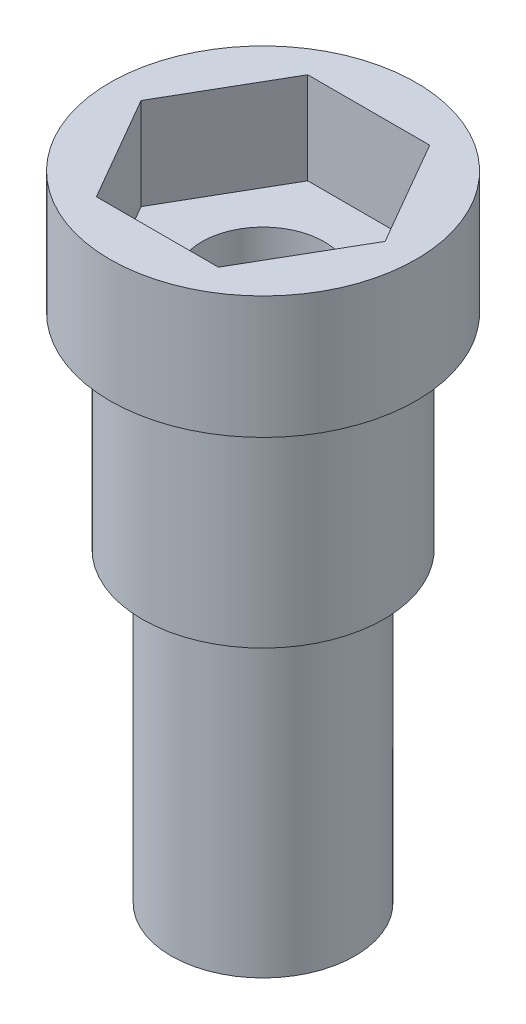
SolidWorks part; units mm, degrees
ref_plane "Front Plane" through (0, 0, 0) normal (0, 0, 1) x (1, 0, 0)
ref_plane "Top Plane" through (0, 0, 0) normal (0, 1, 0) x (1, 0, 0)
ref_plane "Right Plane" through (0, 0, 0) normal (1, 0, 0) x (0, 0, -1)
sketch "Sketch1" plane through (0, 0, 0) normal (0, 1, 0) x (1, 0, 0)
  circle A0 centre (0, 0) radius 3
  circle A1 centre (0, 0) radius 2
  dimension "D1" = 6
  dimension "D2" = 4
extrude "Boss-Extrude1" add sketch "Sketch1" along normal blind 18
sketch "Sketch2" plane through (0, 18, 0) normal (0, 1, 0) x (1, 0, 0)
  circle A0 centre (0, 0) radius 2
  circle A1 centre (0, 0) radius 3.95
  dimension "D1" = 4
  dimension "D2" = 7.9
extrude "Boss-Extrude3" add sketch "Sketch2" along normal blind 6.7 from offset 8 offset against normal yes
sketch "Sketch4" plane through (0, 16.7, 0) normal (0, 1, 0) x (1, 0, 0)
  circle A0 centre (0, 0) radius 2 construction
  circle A1 centre (0, 0) radius 2
  circle A2 centre (0, 0) radius 5
  dimension "D1" = 10
extrude "Boss-Extrude4" add sketch "Sketch4" along normal blind 4
sketch "Sketch5" plane through (0, 20.7, 0) normal (0, 1, 0) x (1, 0, 0)
  line L1 (3.9837, 0) -> (1.9919, 3.45)
  line L2 (1.9919, 3.45) -> (-1.9919, 3.45)
  line L3 (-1.9919, 3.45) -> (-3.9837, 0)
  line L4 (-3.9837, 0) -> (-1.9919, -3.45)
  line L5 (-1.9919, -3.45) -> (1.9919, -3.45)
  line L6 (1.9919, -3.45) -> (3.9837, 0)
  circle A0 centre (0, 0) radius 3.45 construction
  dimension "D1" = 6.9
extrude "Cut-Extrude1" cut sketch "Sketch5" against normal blind 3 contours L1 L2 L3 L4 L5 L6
